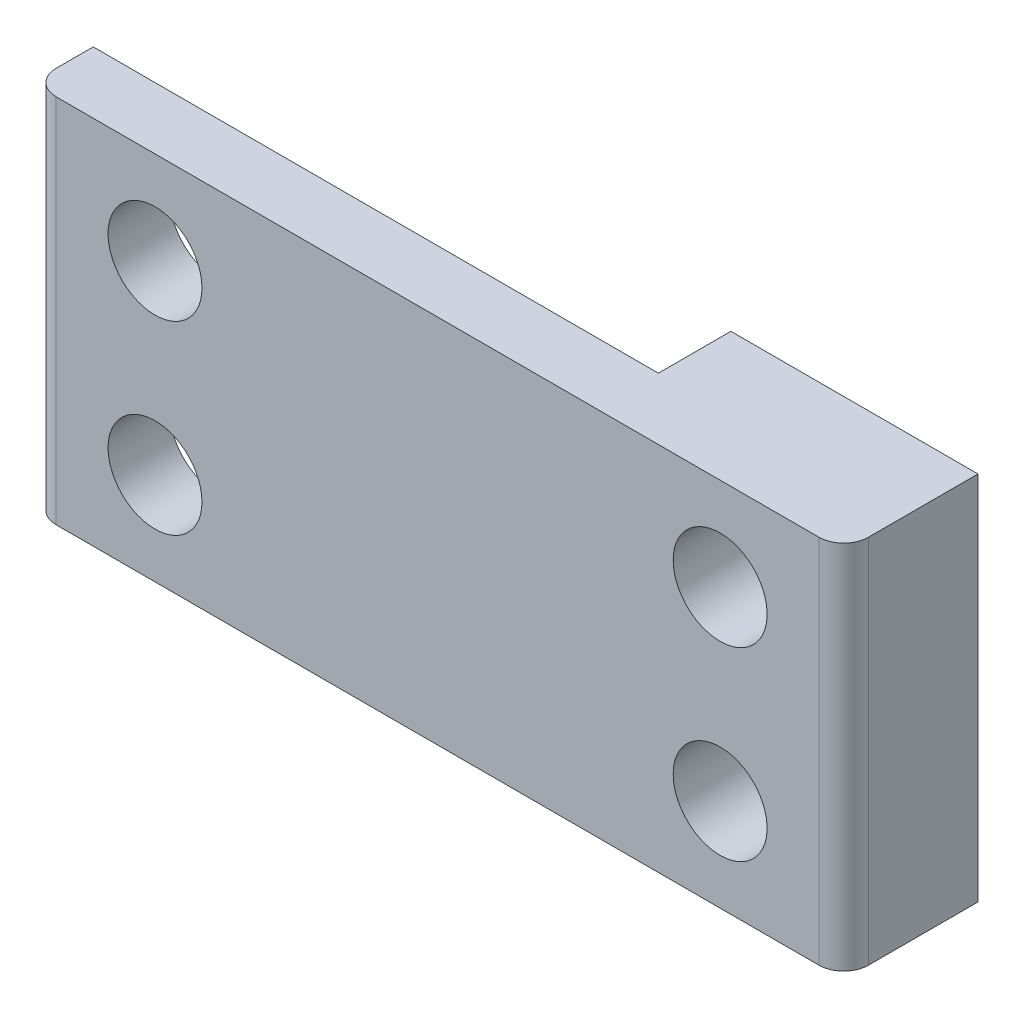
SolidWorks part; units mm, degrees
ref_plane "Front Plane" through (0, 0, 0) normal (0, 0, 1) x (1, 0, 0)
ref_plane "Top Plane" through (0, 0, 0) normal (0, 1, 0) x (1, 0, 0)
ref_plane "Right Plane" through (0, 0, 0) normal (1, 0, 0) x (0, 0, -1)
sketch "Sketch1" plane through (0, 0, 0) normal (0, 0, 1) x (1, 0, 0)
  line L1 (-41.7449, -19.05) -> (41.7449, -19.05)
  line L2 (-41.7449, -19.05) -> (-41.7449, 19.05)
  line L3 (-41.7449, 19.05) -> (41.7449, 19.05)
  line L4 (41.7449, -19.05) -> (41.7449, 19.05)
  line L5 (-41.7449, -19.05) -> (41.7449, 19.05) construction
  line L6 (-41.7449, 19.05) -> (41.7449, -19.05) construction
  point P0 (0, 0)
  dimension "D1" = 83.4898
  dimension "D2" = 38.1
extrude "Boss-Extrude1" add sketch "Sketch1" along normal blind 6.35
sketch "Sketch2" plane through (0, 0, 0) normal (0, 0, -1) x (-1, 0, 0)
  line L0 (41.7449, -19.05) -> (-41.7449, -19.05) construction
  line L1 (-41.7449, 19.05) -> (-16.3449, 19.05)
  line L2 (-41.7449, 19.05) -> (-41.7449, -19.05)
  line L3 (-41.7449, -19.05) -> (-16.3449, -19.05)
  line L4 (-16.3449, 19.05) -> (-16.3449, -19.05)
  dimension "D1" = 25.4
extrude "Boss-Extrude2" add sketch "Sketch2" along normal blind 7.4549
sketch "Sketch6" plane through (0, 0, -7.4549) normal (0, 0, -1) x (-1, 0, 0)
  line L0 (-16.3449, 0) -> (-41.7449, 0) construction
  line L1 (-16.3449, -19.05) -> (-16.3449, 19.05) construction
  line L2 (-41.7449, 19.05) -> (-41.7449, -19.05) construction
  circle A0 centre (-29.0449, 9.525) radius 4.826
  circle A1 centre (-29.0449, -9.525) radius 4.826
  dimension "D1" = 9.525
  dimension "D3" = 9.652
  dimension "D2" = 12.7
extrude "Cut-Extrude1" cut sketch "Sketch6" against normal through all and the other way through all
sketch "Sketch8" plane through (0, 0, 6.35) normal (0, 0, 1) x (1, 0, 0)
  line L0 (-41.7449, 0) -> (41.7449, 0) construction
  line L1 (-41.7449, 19.05) -> (-41.7449, -19.05) construction
  line L2 (41.7449, -19.05) -> (41.7449, 19.05) construction
  circle A0 centre (-29.0449, -9.525) radius 4.826
  circle A1 centre (-29.0449, 9.525) radius 4.826
  dimension "D3" = 9.652
  dimension "D1" = 12.7
  dimension "D2" = 9.525
extrude "Cut-Extrude2" cut sketch "Sketch8" against normal through all
fillet "Fillet1" radius 2.54 2 edges at (-41.7449, 0, 6.35) (41.7449, 0, 6.35)
